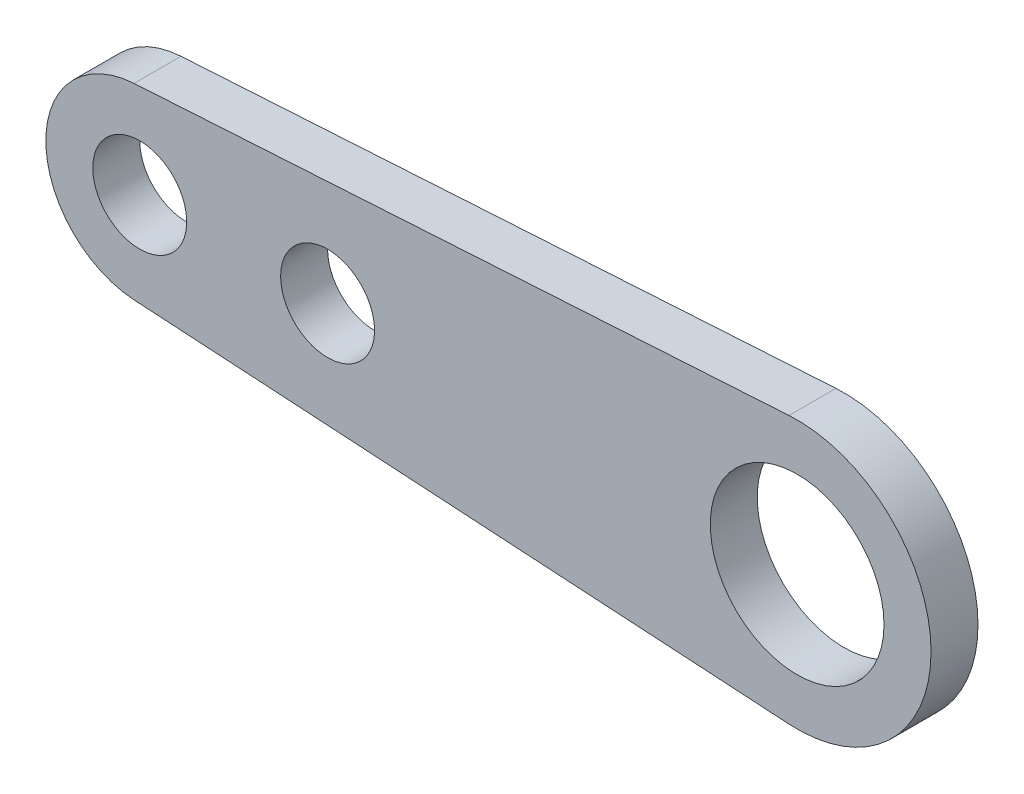
SolidWorks part; units mm, degrees
ref_plane "Front Plane" through (0, 0, 0) normal (1, 0, 0) x (0, 1, 0)
ref_plane "Top Plane" through (0, 0, 0) normal (0, 0, 1) x (0, 1, 0)
ref_plane "Right Plane" through (0, 0, 0) normal (0, 1, 0) x (-1, 0, 0)
sketch "Sketch1" plane through (0, 0, 0) normal (0, 0, 1) x (-1, 0, 0)
  line L0 (0, 0) -> (10.015, 0)
  line L16 (169.7314, 19.963) -> (30.2493, 28.4622)
  line L17 (188.515, 0) -> (178.515, 0)
  line L18 (188.515, 0) -> (188.515, 10) construction
  line L19 (71.0465, 10) -> (12.0572, 10) construction
  line L21 (138.515, 0) -> (158.515, 0)
  line L24 (47.015, 0) -> (118.515, 0)
  arc A10 (47.015, 0) -> (10.015, 0) centre (28.515, 0) ccw
  arc A11 (118.515, 0) -> (138.515, 0) centre (128.515, 0) cw
  arc A12 (158.515, 0) -> (178.515, 0) centre (168.515, 0) cw
  arc A13 (188.515, 0) -> (169.7314, 19.963) centre (168.515, 0) ccw
  arc A14 (30.2493, 28.4622) -> (0, 0) centre (28.515, 0) ccw
  dimension "D4" = 10
  dimension "D5" = 10
  dimension "D7" = 10
  dimension "D9" = 10
  dimension "D11" = 10.015
  dimension "D2" = 37
  dimension "D3" = 100
  dimension "D6" = 40
extrude "Boss-Extrude1" add sketch "Sketch1" along normal blind 10 contours A14 L0 A10 L24 A11 L21 A12 L17 A13 L16
mirror "Mirror1" about plane through (-47.015, 0, 10) normal (0, -1, 0) of "Boss-Extrude1"
ref_plane "Plane1" through (-28.515, 0, 0) normal (1, 0, 0) x (0, 0, -1)
equation "\"BearingBore\"=4"
equation "\"D4@Sketch1\"=\"BearingDiameter\""
equation "\"D5@Sketch1\"=\"BearingDiameter\""
equation "\"MinShinWidth\"= 20"
equation "\"D9@Sketch1\"=\"MinShinWidth\"/2"
equation "\"D2@Sketch1\" = \"MotorDiameter\""
equation "\"ShinThickness\"=10"
equation "\"PivotDistance\"=40"
equation "\"ThighLength\"= 200"
equation "\"HipBore\"=27"
equation "\"ThighThickness\"=20"
equation "\"MaxBending\"=135"
equation "\"MaxStretchingAngle\"= 140"
equation "\"ThighJointDistance\"=157.485"
equation "\"MotorDiameter\"=37"
equation "\"ShinLength\"=100"
equation "\"D3@Sketch1\"=\"ShinLength\""
equation "\"BearingDiameter\"= 10"
equation "\"D1@Boss-Extrude1\"=\"ShinThickness\""
equation "\"D6@Sketch1\"=\"PivotDistance\""
